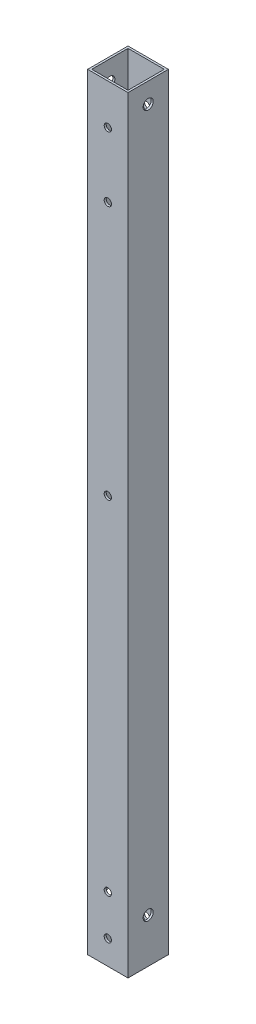
SolidWorks part; units mm, degrees
ref_plane "Front Plane" through (0, 0, 0) normal (0, 0, 1) x (1, 0, 0)
ref_plane "Top Plane" through (0, 0, 0) normal (0, 1, 0) x (1, 0, 0)
ref_plane "Right Plane" through (0, 0, 0) normal (1, 0, 0) x (0, 0, -1)
sketch "Sketch1" plane through (0, 0, 0) normal (0, 1, 0) x (1, 0, 0)
  line L0 (0, 0) -> (0, 25.4)
  line L1 (0, 25.4) -> (25.4, 25.4)
  line L2 (25.4, 25.4) -> (25.4, 0)
  line L3 (25.4, 0) -> (0, 0)
  line L6 (1.27, 12.3615) -> (1.27, 24.13)
  line L7 (1.27, 24.13) -> (12.7, 24.13)
  line L10 (12.7, 24.13) -> (24.13, 24.13)
  line L11 (24.13, 24.13) -> (24.13, 12.7)
  line L12 (24.13, 1.27) -> (24.13, 12.7)
  line L13 (24.13, 1.27) -> (12.7, 1.27)
  line L14 (1.27, 1.27) -> (12.7, 1.27)
  line L15 (1.27, 12.3615) -> (1.27, 1.27)
  dimension "D1" = 25.4
  dimension "D2" = 25.4
  dimension "D3" = 11.7685
  dimension "D4" = 11.0915
  dimension "D5" = 11.43
  dimension "D6" = 11.43
extrude "Boss-Extrude1" add sketch "Sketch1" along normal blind 482.6
sketch "Sketch2" plane through (0, 0, -25.4) normal (0, 0, -1) x (-1, 0, 0)
  line L0 (-25.4, 482.6) -> (0, 482.6) construction
  line L1 (-25.4, 482.6) -> (-25.4, 0) construction
  circle A0 centre (-12.7, 416.56) radius 2.286
  dimension "D3" = 4.572
  dimension "D1" = 66.04
  dimension "D2" = 12.7
extrude "Cut-Extrude1" cut sketch "Sketch2" against normal through all
sketch "Sketch3" plane through (0, 0, -25.4) normal (0, 0, -1) x (-1, 0, 0)
  line L1 (-25.4, 482.6) -> (-25.4, 0) construction
  line L2 (-25.4, 482.6) -> (0, 482.6) construction
  circle A0 centre (-12.7, 40.64) radius 2.286
  dimension "D3" = 4.572
  dimension "D1" = 441.96
  dimension "D2" = 12.7
extrude "Cut-Extrude2" cut sketch "Sketch3" against normal through all
sketch "Sketch4" plane through (0, 0, -25.4) normal (0, 0, -1) x (-1, 0, 0)
  line L0 (-25.4, 482.6) -> (0, 482.6) construction
  line L1 (-25.4, 482.6) -> (-25.4, 0) construction
  circle A0 centre (-12.7, 256.54) radius 2.286
  dimension "D2" = 4.572
  dimension "D1" = 226.06
  dimension "D3" = 12.7
extrude "Cut-Extrude3" cut sketch "Sketch4" against normal through all
sketch "Sketch6" plane through (0, 0, -25.4) normal (0, 0, -1) x (-1, 0, 0)
  line L0 (-25.4, 482.6) -> (-25.4, 0) construction
  line L1 (-25.4, 482.6) -> (0, 482.6) construction
  circle A0 centre (-12.7, 457.2) radius 2.286
  dimension "D3" = 4.572
  dimension "D1" = 12.7
  dimension "D2" = 25.4
extrude "Cut-Extrude5" cut sketch "Sketch6" against normal through all
sketch "Sketch7" plane through (0, 0, -25.4) normal (0, 0, -1) x (-1, 0, 0)
  line L0 (-25.4, 482.6) -> (-25.4, 0) construction
  line L1 (-25.4, 0) -> (0, 0) construction
  circle A0 centre (-12.7, 15.24) radius 2.286
  dimension "D3" = 4.572
  dimension "D1" = 12.7
  dimension "D2" = 15.24
extrude "Cut-Extrude6" cut sketch "Sketch7" against normal through all
sketch "Sketch8" plane through (0, 0, 0) normal (-1, 0, 0) x (0, 0, 1)
  line L0 (-25.4, 482.6) -> (-25.4, 0) construction
  line L1 (-25.4, 482.6) -> (0, 482.6) construction
  circle A0 centre (-12.7, 469.9) radius 3.175
  dimension "D3" = 6.35
  dimension "D1" = 12.7
  dimension "D2" = 12.7
extrude "Cut-Extrude7" cut sketch "Sketch8" against normal through all
sketch "Sketch9" plane through (0, 0, 0) normal (-1, 0, 0) x (0, 0, 1)
  line L0 (0, 482.6) -> (0, 0) construction
  line L1 (-25.4, 0) -> (0, 0) construction
  circle A0 centre (-12.7, 27.94) radius 3.175
  dimension "D3" = 6.35
  dimension "D1" = 12.7
  dimension "D2" = 27.94
extrude "Cut-Extrude8" cut sketch "Sketch9" against normal through all
